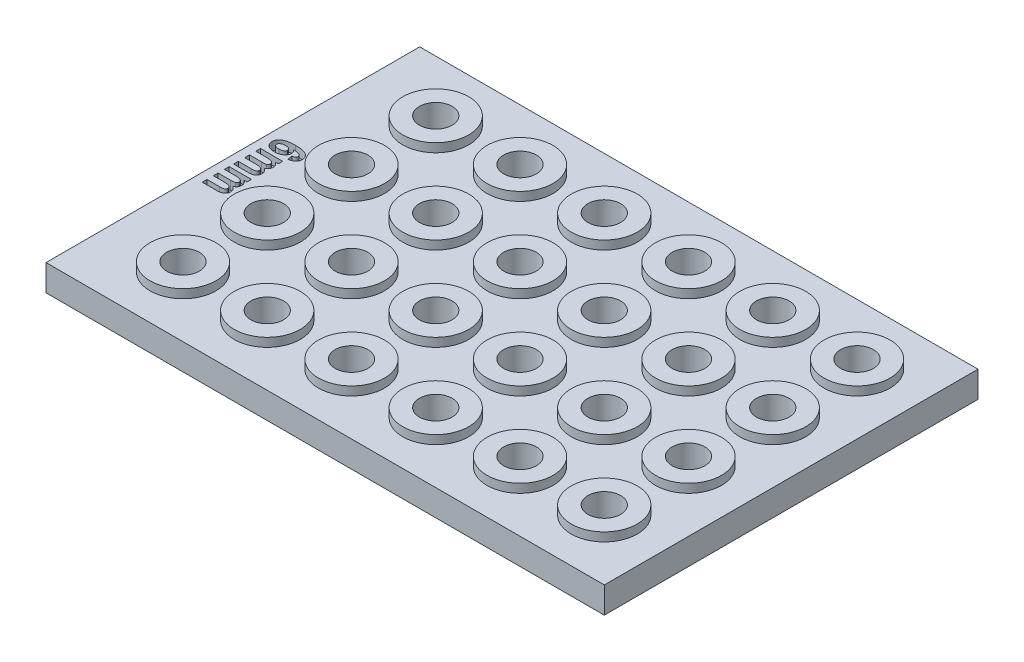
SolidWorks part; units mm, degrees
material "PVC Rigid"
ref_plane "Front Plane" through (0, 0, 0) normal (0, 0, 1) x (1, 0, 0)
ref_plane "Top Plane" through (0, 0, 0) normal (0, 1, 0) x (1, 0, 0)
ref_plane "Right Plane" through (0, 0, 0) normal (1, 0, 0) x (0, 0, -1)
ref_plane "Top of 24 well plate" through (0, 6, 0) normal (0, 1, 0) x (1, 0, 0)
ref_plane "Bottom of 24 well plate" through (0, 23.5, 0) normal (0, 1, 0) x (1, 0, 0)
ref_plane "Middle of 24 well plate" through (0, 14.75, 0) normal (0, 1, 0) x (1, 0, 0)
sketch "Sketch1" plane through (0, 0, 0) normal (0, 1, 0) x (1, 0, 0)
  line L1 (-63.945, 42.8) -> (63.945, 42.8)
  line L2 (-63.945, 42.8) -> (-63.945, -42.8)
  line L3 (-63.945, -42.8) -> (63.945, -42.8)
  line L4 (63.945, 42.8) -> (63.945, -42.8)
  line L5 (-63.945, 42.8) -> (63.945, -42.8) construction
  line L6 (-63.945, -42.8) -> (63.945, 42.8) construction
  point P0 (0, 0)
  dimension "D1" = 127.89
  dimension "D2" = 85.6
extrude "Main Plate" add sketch "Sketch1" along normal up to surface (6 mm away) up to plane "Top of 24 well plate"
sketch "Wells_LSP" plane through (0, 6, 0) normal (0, 1, 0) x (1, 0, 0)
  line L0 (-46.425, 28.96) -> (-27.125, 28.96) construction
  line L4 (63.945, 42.8) -> (-63.945, 42.8) construction
  line L5 (-63.945, 42.8) -> (-63.945, -42.8) construction
  circle A0 centre (-46.425, 28.96) radius 7.56
  circle A1 centre (-27.125, 28.96) radius 7.56
  circle A2 centre (-7.825, 28.96) radius 7.56
  circle A3 centre (11.475, 28.96) radius 7.56
  circle A4 centre (30.775, 28.96) radius 7.56
  circle A5 centre (50.075, 28.96) radius 7.56
  circle A6 centre (-27.125, 9.66) radius 7.56
  circle A7 centre (-7.825, 9.66) radius 7.56
  circle A8 centre (11.475, 9.66) radius 7.56
  circle A9 centre (30.775, 9.66) radius 7.56
  circle A10 centre (50.075, 9.66) radius 7.56
  circle A11 centre (-27.125, -9.64) radius 7.56
  circle A12 centre (-7.825, -9.64) radius 7.56
  circle A13 centre (11.475, -9.64) radius 7.56
  circle A14 centre (30.775, -9.64) radius 7.56
  circle A15 centre (50.075, -9.64) radius 7.56
  circle A16 centre (-27.125, -28.94) radius 7.56
  circle A17 centre (-7.825, -28.94) radius 7.56
  circle A18 centre (11.475, -28.94) radius 7.56
  circle A19 centre (30.775, -28.94) radius 7.56
  circle A20 centre (50.075, -28.94) radius 7.56
  circle A21 centre (-46.425, 9.66) radius 7.56
  circle A22 centre (-46.425, -9.64) radius 7.56
  circle A23 centre (-46.425, -28.94) radius 7.56
  dimension "D2" = 6
  dimension "D4" = 4
  dimension "D7" = 15.12
  dimension "D16" = 17.52
  dimension "D3" = 19.3
  dimension "D15" = 13.84
extrude "Boss-Extrude1" add sketch "Wells_LSP" along normal blind 2
ref_point "Point1"
ref_plane "Plane1" through (0, 0, -28.96) normal (0, 0, -1) x (-1, 0, 0)
sketch "Sketch2" plane through (0, 0, -28.96) normal (0, 0, -1) x (-1, 0, 0)
  line L0 (46.425, 8) -> (46.425, 0) construction
  line L1 (46.425, 23.5) -> (50.175, 23.5)
  line L2 (46.425, 23.5) -> (46.425, 0)
  line L3 (46.425, 0) -> (50.175, 0)
  line L4 (50.175, 23.5) -> (50.175, 0)
  line L5 (53.985, 8) -> (38.865, 8) construction
  line L6 (-63.945, 0) -> (63.945, 0) construction
  line L7 (47.08, 23.5) -> (-47.08, 23.5) construction
  line L8 (55, 14.75) -> (-55, 14.75) construction
  line L9 (47.08, 6) -> (-47.08, 6) construction
  point P10 (50.175, 6)
  point P13 (46.425, 14.75)
  point P16 (0, 0)
  point P19 (0, 0)
  dimension "D1" = 0
  dimension "D2" = 3.75
revolve "Cut-Revolve1" cut sketch "Sketch2" angle 360 about L2
pattern_linear "LPattern1" count 4 spacing 19.3 along (0, 0, 1) count 6 spacing 19.3 along (1, 0, 0) of "Cut-Revolve1"
sketch "Sketch3" plane through (0, 6, 0) normal (0, 1, 0) x (1, 0, 0)
  line L0 (-62.0038, 42.8) -> (-62.0038, -42.8) construction
  line L1 (63.945, 42.8) -> (-63.945, 42.8) construction
  line L2 (-63.945, -42.8) -> (63.945, -42.8) construction
  text T0 "6mm" font "Arial Narrow" height 7
extrude "Cut-Extrude1" cut sketch "Sketch3" against normal blind 2 from surface at 0 starting at face at (-46.425, 6, 36.5)
equation "\"D1\"= 0.32"
equation "\"D1\"= 1.27 - 0.32"
